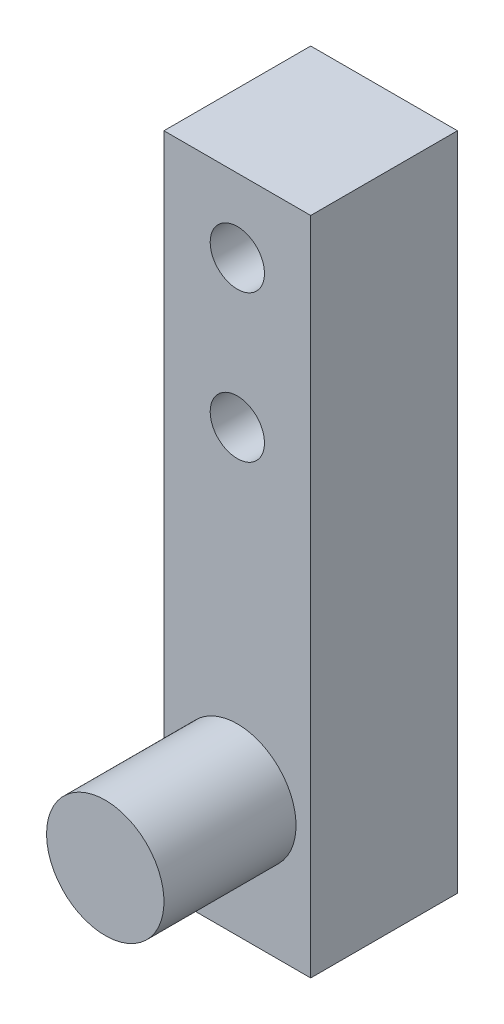
SolidWorks part; units mm, degrees
ref_plane "Plan de face" through (0, 0, 0) normal (0, 0, 1) x (1, 0, 0)
ref_plane "Plan de dessus" through (0, 0, 0) normal (0, 1, 0) x (1, 0, 0)
ref_plane "Plan de droite" through (0, 0, 0) normal (1, 0, 0) x (0, 0, -1)
sketch "Esquisse1" plane through (0, 0, 0) normal (0, 1, 0) x (1, 0, 0)
  line L1 (-5, -5) -> (5, -5)
  line L2 (-5, -5) -> (-5, 5)
  line L3 (-5, 5) -> (5, 5)
  line L4 (5, -5) -> (5, 5)
  line L5 (-5, -5) -> (5, 5) construction
  line L6 (-5, 5) -> (5, -5) construction
  point P0 (0, 0)
  dimension "D1" = 10
extrude "Boss.-Extru.1" add sketch "Esquisse1" along normal blind 20 contours L1 L4 L3 L2
sketch "Esquisse5" plane through (0, 0, -5) normal (0, 0, -1) x (-1, 0, 0)
  line L0 (0, 0) -> (0, 10) construction
  line L1 (5, 0) -> (-5, 0) construction
  line L3 (-5, 10) -> (5, 10) construction
  line L4 (-5, 20) -> (-5, 0) construction
  line L5 (5, 20) -> (5, 0) construction
  circle A0 centre (0, 15) radius 1.7948
  circle A2 centre (0, 5) radius 1.7948
hole_wizard "Dégagement M3.51" positions "Esquisse6" profile "Esquisse7" hole size "M3.5" standard "ISO" end condition through all
sketch "Esquisse6" plane through (0, 0, -5) normal (0, 0, -1) x (-1, 0, 0)
  point P0 (0, 15)
  point P3 (0, 5)
sketch "Esquisse7" plane through (0, 15, -5) normal (1, 0, 0) x (0, 1, 0)
  line L0 (0, 0) -> (0, 10)
  line L1 (0, 10) -> (1.85, 10)
  line L2 (1.85, 10) -> (1.85, 0)
  line L5 (1.85, 0) -> (0, 0)
  line L11 (0, -6.35) -> (0, 107.95) construction
  dimension "Diamètre du perçage jusqu'au prochain" = 3.7
  dimension "Profondeur du perçage jusqu'au prochain" = 10
sketch "Esquisse2" plane through (0, 0, 0) normal (0, -1, 0) x (1, 0, 0)
  line L0 (0, 0) -> (0, 5) construction
  line L1 (-5, 5) -> (5, 5) construction
  line L6 (-5, 5) -> (-5, -5)
  line L7 (-5, -5) -> (5, -5)
  line L8 (5, -5) -> (5, 5)
  line L9 (5, 5) -> (-5, 5)
  line L10 (-5, 5) -> (-5, -5)
  line L11 (-5, -5) -> (5, -5)
  line L12 (5, -5) -> (5, 5)
  line L13 (5, 5) -> (-5, 5)
  dimension "D1" = 0
extrude "Boss.-Extru.2" add sketch "Esquisse2" along normal blind 25
sketch "Esquisse4" plane through (0, -15, 5) normal (0, 0, -1) x (1, 0, 0)
  line L0 (0, 1.5) -> (0, 10) construction
  line L1 (5, 10) -> (-5, 10) construction
  line L2 (0, -35) -> (0, -15) construction
  line L4 (0, -15) -> (0, 10) construction
  line L5 (-5, -35) -> (5, -35) construction
  circle A0 centre (0, 1.5) radius 4
  dimension "D1" = 8
  dimension "D2" = 16.5
extrude "Boss.-Extru.3" add sketch "Esquisse4" against normal blind 9
